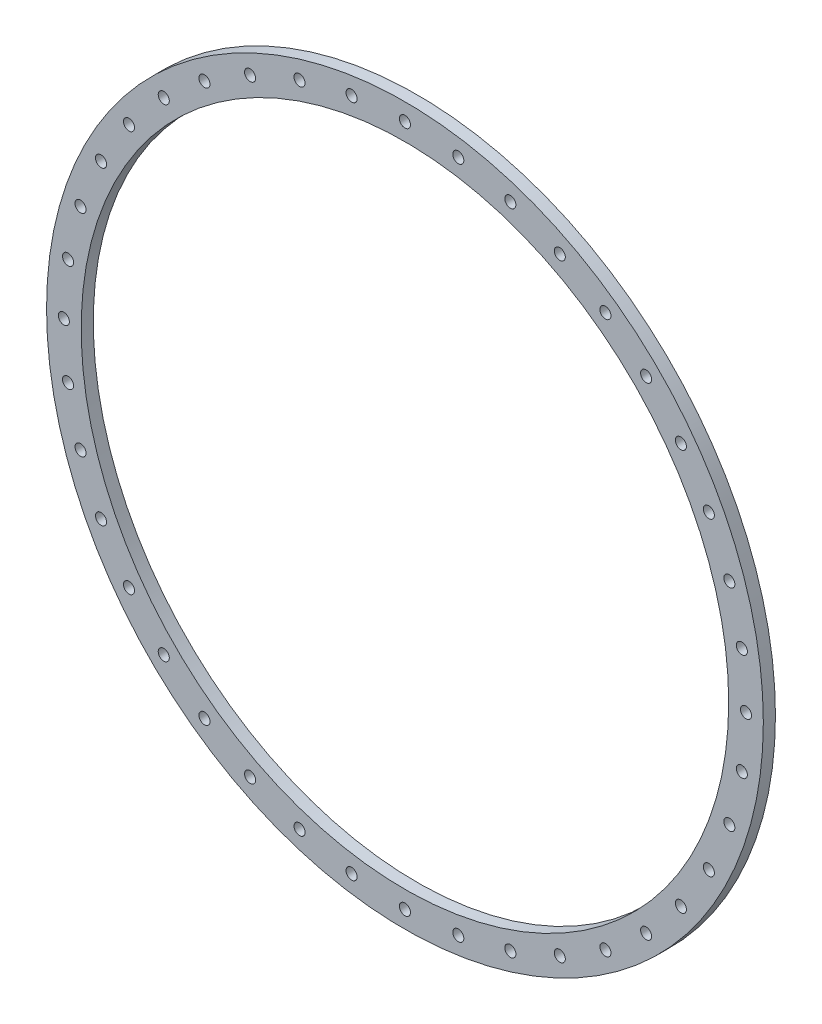
SolidWorks part; units mm, degrees
material "ABS"
ref_plane "前视基准面" through (0, 0, 0) normal (0, 0, 1) x (1, 0, 0)
ref_plane "上视基准面" through (0, 0, 0) normal (0, 1, 0) x (1, 0, 0)
ref_plane "右视基准面" through (0, 0, 0) normal (1, 0, 0) x (0, 0, -1)
sketch "草图1" plane through (0, 0, 0) normal (0, 0, 1) x (1, 0, 0)
  circle A0 centre (0, 0) radius 93.5
  circle A1 centre (0, 0) radius 103.5
  circle A2 centre (0, 0) radius 98.5 construction
  circle A3 centre (0, 98.5) radius 1.6
  circle A4 centre (15.4088, 97.2873) radius 1.6
  circle A5 centre (30.4382, 93.6791) radius 1.6
  circle A6 centre (44.7181, 87.7641) radius 1.6
  circle A7 centre (57.8968, 79.6882) radius 1.6
  circle A8 centre (69.65, 69.65) radius 1.6
  circle A9 centre (79.6882, 57.8968) radius 1.6
  circle A10 centre (87.7641, 44.7181) radius 1.6
  circle A11 centre (93.6791, 30.4382) radius 1.6
  circle A12 centre (97.2873, 15.4088) radius 1.6
  circle A13 centre (98.5, 0) radius 1.6
  circle A14 centre (97.2873, -15.4088) radius 1.6
  circle A15 centre (93.6791, -30.4382) radius 1.6
  circle A16 centre (87.7641, -44.7181) radius 1.6
  circle A17 centre (79.6882, -57.8968) radius 1.6
  circle A18 centre (69.65, -69.65) radius 1.6
  circle A19 centre (57.8968, -79.6882) radius 1.6
  circle A20 centre (44.7181, -87.7641) radius 1.6
  circle A21 centre (30.4382, -93.6791) radius 1.6
  circle A22 centre (15.4088, -97.2873) radius 1.6
  circle A23 centre (0, -98.5) radius 1.6
  circle A24 centre (-15.4088, -97.2873) radius 1.6
  circle A25 centre (-30.4382, -93.6791) radius 1.6
  circle A26 centre (-44.7181, -87.7641) radius 1.6
  circle A27 centre (-57.8968, -79.6882) radius 1.6
  circle A28 centre (-69.65, -69.65) radius 1.6
  circle A29 centre (-79.6882, -57.8968) radius 1.6
  circle A30 centre (-87.7641, -44.7181) radius 1.6
  circle A31 centre (-93.6791, -30.4382) radius 1.6
  circle A32 centre (-97.2873, -15.4088) radius 1.6
  circle A33 centre (-98.5, 0) radius 1.6
  circle A34 centre (-97.2873, 15.4088) radius 1.6
  circle A35 centre (-93.6791, 30.4382) radius 1.6
  circle A36 centre (-87.7641, 44.7181) radius 1.6
  circle A37 centre (-79.6882, 57.8968) radius 1.6
  circle A38 centre (-69.65, 69.65) radius 1.6
  circle A39 centre (-57.8968, 79.6882) radius 1.6
  circle A40 centre (-44.7181, 87.7641) radius 1.6
  circle A41 centre (-30.4382, 93.6791) radius 1.6
  circle A42 centre (-15.4088, 97.2873) radius 1.6
  point P7 (123.0838, 14.7338)
  point P8 (0, 0)
  point P88 (0, 0)
  dimension "D1" = 187
  dimension "D2" = 207
  dimension "D3" = 197
  dimension "D4" = 3.2
  dimension "D5" = 40
extrude "凸台-拉伸1" add sketch "草图1" along normal blind 3.5
